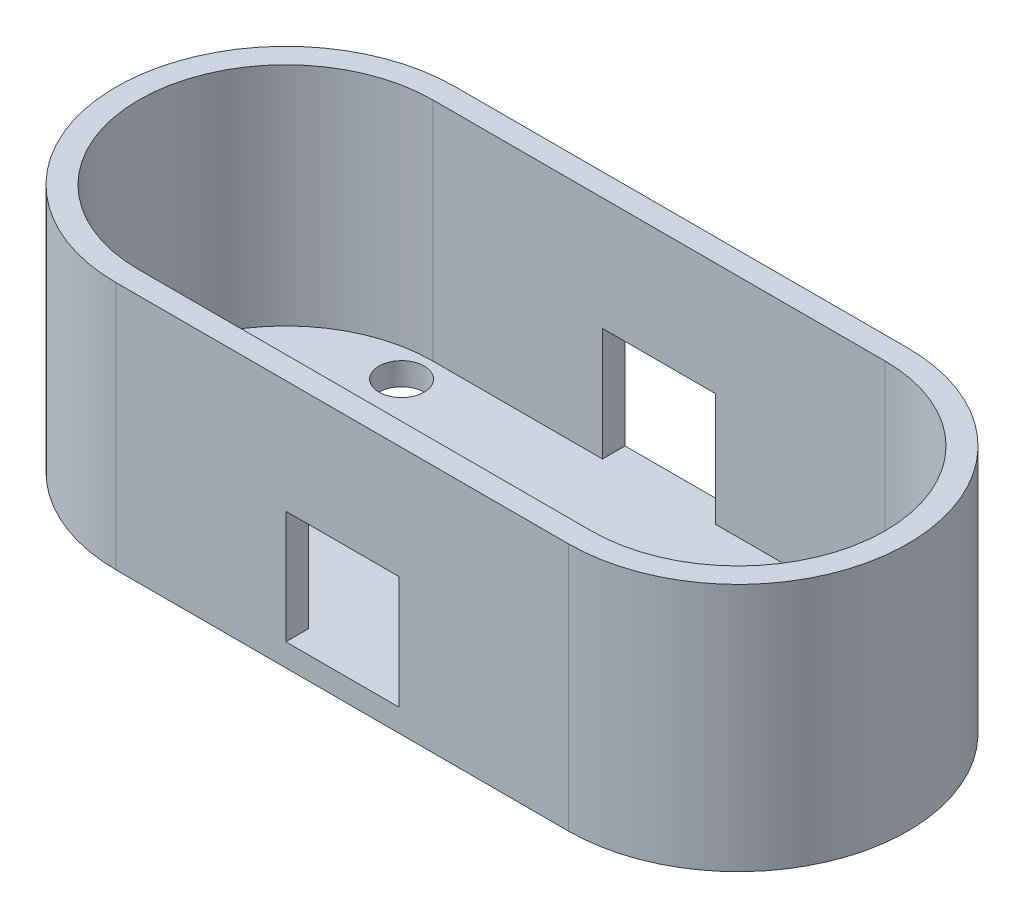
SolidWorks part; units mm, degrees
ref_plane "Front Plane" through (0, 0, 0) normal (0, 0, 1) x (1, 0, 0)
ref_plane "Top Plane" through (0, 0, 0) normal (0, 1, 0) x (1, 0, 0)
ref_plane "Right Plane" through (0, 0, 0) normal (1, 0, 0) x (0, 0, -1)
sketch "Sketch2" plane through (0, 0, 0) normal (0, 1, 0) x (1, 0, 0)
  line L0 (0, 0) -> (25.4, 0) construction
  line L5 (0, 9.525) -> (25.4, 9.525)
  line L6 (0, -9.525) -> (25.4, -9.525)
  line L7 (0, 0) -> (25.4, 0) construction
  line L8 (0, 8.255) -> (25.4, 8.255)
  line L9 (0, -8.255) -> (25.4, -8.255)
  arc A0 (0, 9.525) -> (0, -9.525) centre (0, 0) ccw
  arc A1 (25.4, -9.525) -> (25.4, 9.525) centre (25.4, 0) ccw
  arc A2 (0, 8.255) -> (0, -8.255) centre (0, 0) ccw
  arc A3 (25.4, -8.255) -> (25.4, 8.255) centre (25.4, 0) ccw
  point P2 (12.7, 0)
  point P10 (12.7, 0)
  dimension "D3" = 16.51
  dimension "D1" = 19.05
  dimension "D2" = 25.4
  dimension "D4" = 25.4
extrude "Boss-Extrude1" add sketch "Sketch2" along normal blind 12.7
sketch "Sketch3" plane through (0, 0, 0) normal (0, -1, 0) x (1, 0, 0)
  line L0 (0, 0) -> (25.4, 0) construction
  line L1 (0, 9.525) -> (25.4, 9.525)
  line L2 (0, -9.525) -> (25.4, -9.525)
  arc A0 (0, 9.525) -> (0, -9.525) centre (0, 0) ccw
  arc A1 (25.4, -9.525) -> (25.4, 9.525) centre (25.4, 0) ccw
  point P4 (12.7, 0)
  dimension "D1" = 19.05
  dimension "D2" = 25.4
extrude "Boss-Extrude2" add sketch "Sketch3" along normal blind 1.27
sketch "Sketch4" plane through (0, 0, 9.525) normal (0, 0, 1) x (1, 0, 0)
  line L0 (12.7, 12.7) -> (12.7, -1.27) construction
  line L1 (0, 12.7) -> (25.4, 12.7) construction
  line L2 (25.4, -1.27) -> (0, -1.27) construction
  line L3 (0, 5.715) -> (25.4, 5.715) construction
  line L4 (0, 12.7) -> (0, -1.27) construction
  line L5 (25.4, 12.7) -> (25.4, -1.27) construction
  line L7 (9.525, 0) -> (15.875, 0)
  line L8 (9.525, 0) -> (9.525, 6.35)
  line L9 (9.525, 6.35) -> (15.875, 6.35)
  line L10 (15.875, 0) -> (15.875, 6.35)
  point P12 (12.7, 5.715)
  dimension "D1" = 6.35
  dimension "D2" = 6.35
  dimension "D3" = 6.35
extrude "Cut-Extrude1" cut sketch "Sketch4" against normal through all
sketch "Sketch5" plane through (0, 0, 0) normal (0, 1, 0) x (1, 0, 0)
  circle A0 centre (-6.127, 0) radius 1.27
  circle A1 centre (32.1908, 0) radius 1.27
  circle A2 centre (0, 6.4997) radius 1.27
  circle A3 centre (0, -5.9918) radius 1.27
  circle A4 centre (26.6354, 6.4997) radius 1.27
  circle A5 centre (26.6354, -5.9918) radius 1.27
  point P12 (-3.6199, -3.6153)
  point P13 (27.8539, -5.9918)
  point P14 (27.8539, 6.4997)
  point P15 (32.1908, 0)
  point P16 (0, -5.9918)
  point P17 (0, 6.4997)
  point P18 (26.6354, 6.4997)
  point P19 (26.6354, -5.9918)
  dimension "D1" = 2.54
  dimension "D2" = 2.54
  dimension "D3" = 2.54
  dimension "D4" = 2.54
  dimension "D5" = 2.54
  dimension "D6" = 2.54
extrude "Cut-Extrude2" cut sketch "Sketch5" against normal up to next
